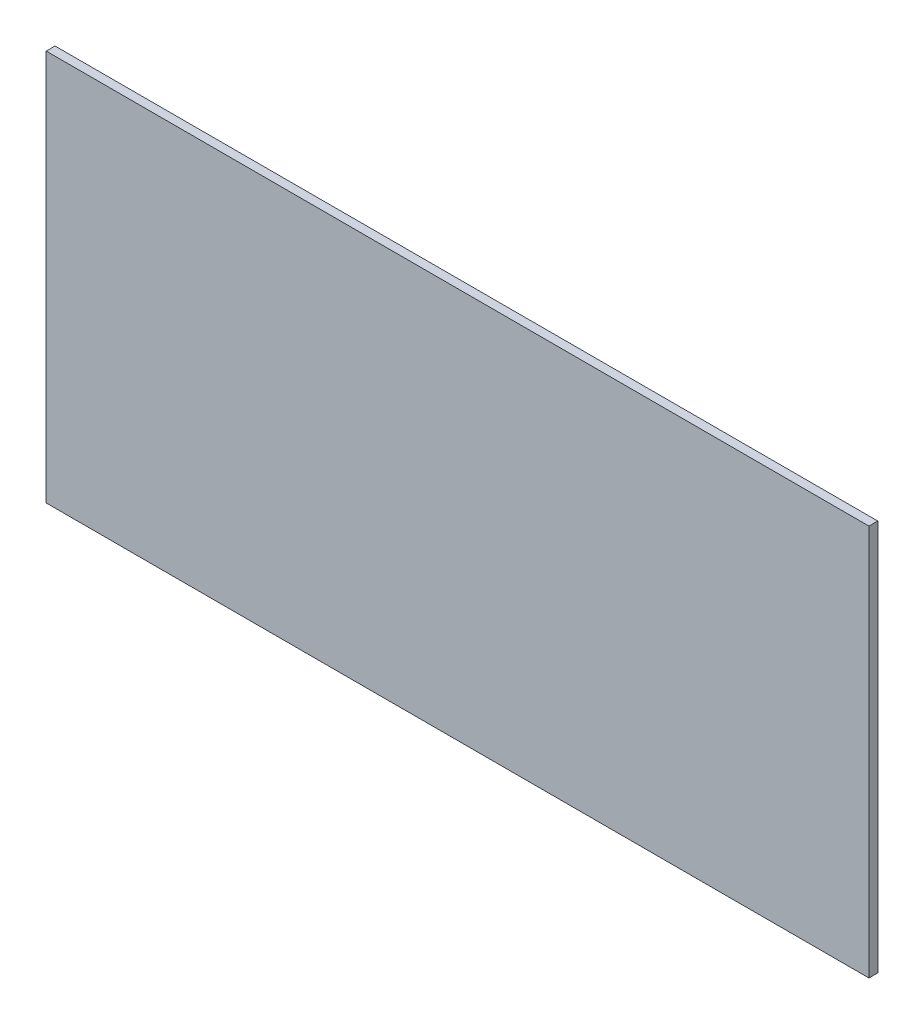
SolidWorks part; units mm, degrees
material "ABS"
ref_plane "Front Plane" through (0, 0, 0) normal (0, 0, 1) x (1, 0, 0)
ref_plane "Top Plane" through (0, 0, 0) normal (0, 1, 0) x (1, 0, 0)
ref_plane "Right Plane" through (0, 0, 0) normal (1, 0, 0) x (0, 0, -1)
sketch "Sketch1" plane through (0, 0, 0) normal (0, 0, 1) x (1, 0, 0)
  line L1 (-233.6, -111.125) -> (233.6, -111.125)
  line L2 (-233.6, -111.125) -> (-233.6, 111.125)
  line L3 (-233.6, 111.125) -> (233.6, 111.125)
  line L4 (233.6, -111.125) -> (233.6, 111.125)
  line L5 (-233.6, -111.125) -> (233.6, 111.125) construction
  line L6 (-233.6, 111.125) -> (233.6, -111.125) construction
  point P0 (0, 0)
  dimension "D1" = 467.2
  dimension "D2" = 222.25
extrude "Boss-Extrude1" add sketch "Sketch1" along normal blind 5
